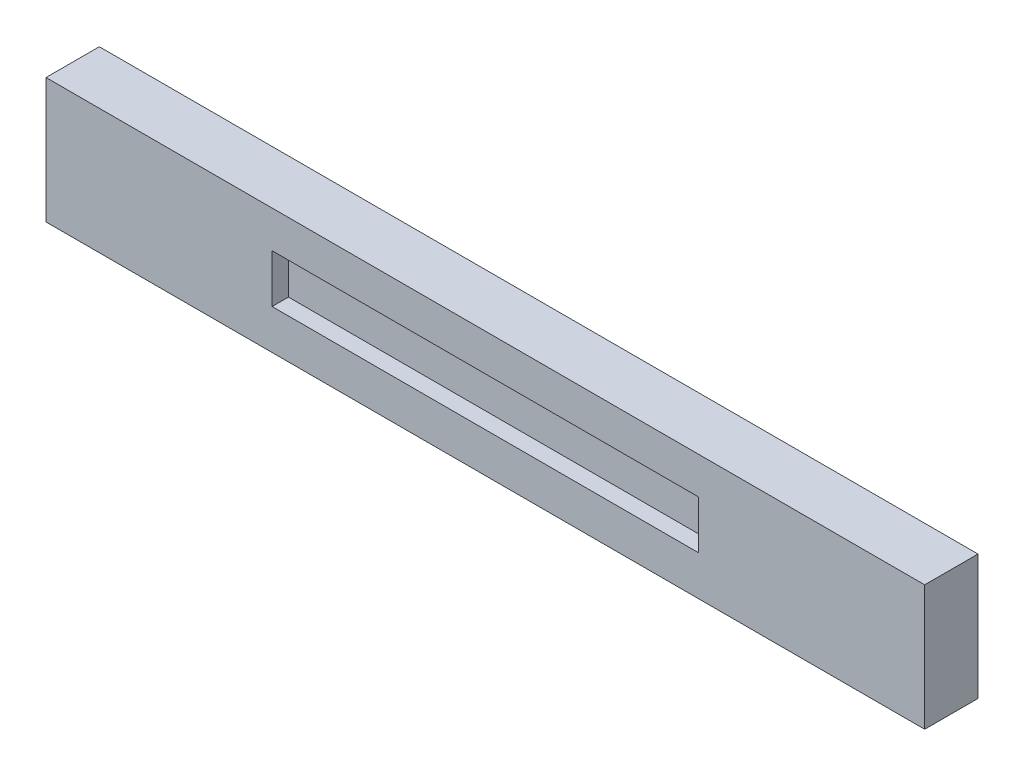
SolidWorks part; units mm, degrees
ref_plane "Front Plane" through (0, 0, 0) normal (0, 0, 1) x (1, 0, 0)
ref_plane "Top Plane" through (0, 0, 0) normal (0, 1, 0) x (1, 0, 0)
ref_plane "Right Plane" through (0, 0, 0) normal (1, 0, 0) x (0, 0, -1)
other "Configuration Table"
sketch "Sketch1" plane through (0, 0, 0) normal (0, 0, 1) x (1, 0, 0)
  line L1 (0, 0) -> (618, 0)
  line L2 (0, 0) -> (0, 88)
  line L3 (0, 88) -> (618, 88)
  line L4 (618, 0) -> (618, 88)
extrude "CEK_donmus_on_pu_37.5_1" add sketch "Sketch1" along normal blind 37.5 from offset 1 separate body
sketch "Sketch2" plane through (0, 0, 0) normal (0, 0, 1) x (1, 0, 0)
  line L1 (159, 28) -> (459, 28)
  line L2 (159, 28) -> (159, 62)
  line L3 (159, 62) -> (459, 62)
  line L4 (459, 28) -> (459, 62)
extrude "CEK_donmus_on_pu_37.5_2" cut sketch "Sketch2" along normal blind 14 from offset 27
